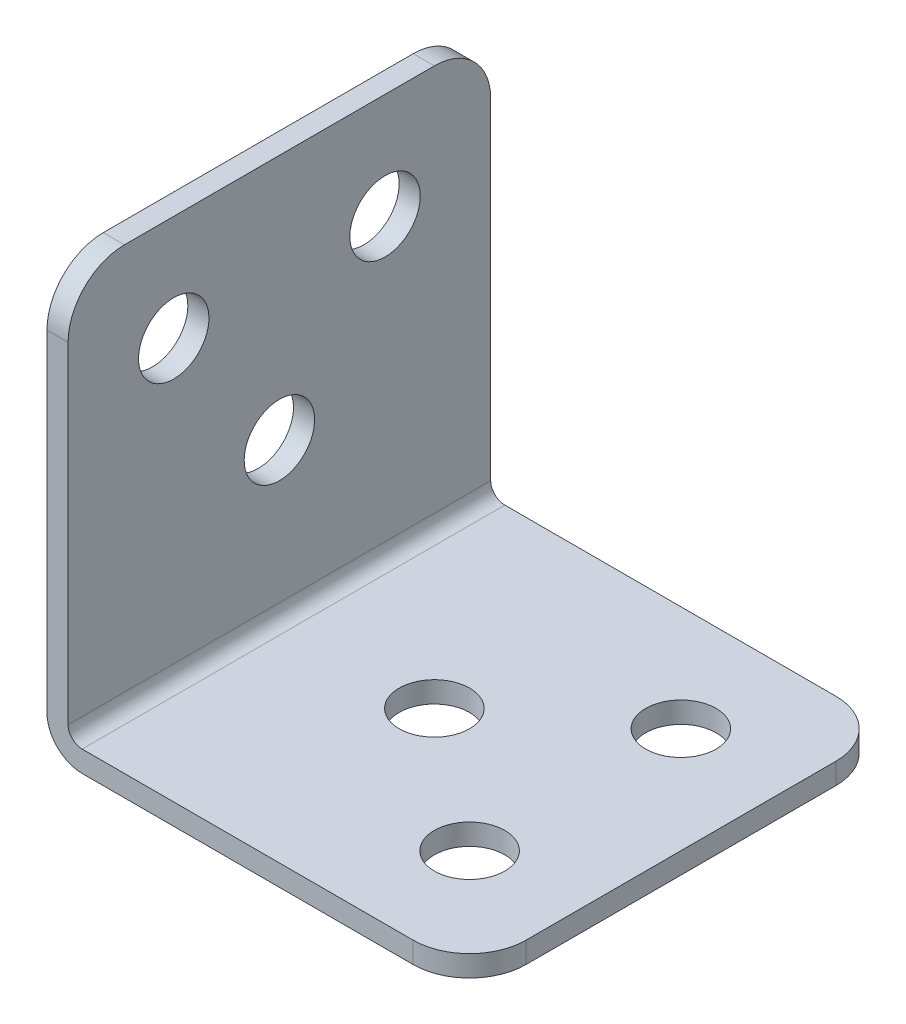
SolidWorks part; units mm, degrees
material "AISI 316 Отожженная нержавеющая сталь. полоса (SS)"
ref_plane "Спереди XY" through (0, 0, 0) normal (0, 0, 1) x (1, 0, 0)
ref_plane "Сверху XZ" through (0, 0, 0) normal (0, 1, 0) x (1, 0, 0)
ref_plane "Справа ZY" through (0, 0, 0) normal (1, 0, 0) x (0, 0, -1)
sketch "Эскиз1" plane through (0, 0, 0) normal (0, 0, 1) x (1, 0, 0)
  line L0 (-2.5, 27.5) -> (-2.5, 0)
  line L1 (0, -2.5) -> (27.5, -2.5)
  line L2 (-1, 27.5) -> (-1, 0)
  line L3 (0, -1) -> (27.5, -1)
  line L4 (-2.5, 27.5) -> (-1, 27.5)
  line L5 (27.5, -1) -> (27.5, -2.5)
  arc A0 (-2.5, 0) -> (0, -2.5) centre (0, 0) ccw
  arc A1 (-1, 0) -> (0, -1) centre (0, 0) ccw
  dimension "D4" = 1
  dimension "D1" = 30
  dimension "D2" = 30
  dimension "D3" = 1.5
extrude "Бобышка-Вытянуть1" add sketch "Эскиз1" along normal blind 30
sketch "Эскиз2" plane through (-2.5, 0, 0) normal (-1, 0, 0) x (0, 0, 1)
  line L0 (15, 27.5) -> (15, -9.5944) construction
  line L1 (30, 27.5) -> (0, 27.5) construction
  line L2 (15, 20) -> (0, 20) construction
  line L6 (0, 27.5) -> (0, 0) construction
  line L7 (30, 27.5) -> (0, 27.5) construction
  circle A0 centre (7.5, 20) radius 2.5
  circle A1 centre (22.5, 20) radius 2.5
  circle A2 centre (15, 10) radius 2.5
  dimension "D1" = 5
  dimension "D4" = 5
  dimension "D2" = 7.5
  dimension "D3" = 17.5
extrude "Вырез-Вытянуть1" cut sketch "Эскиз2" against normal blind 40
sketch "Эскиз3" plane through (0, -2.5, 0) normal (0, -1, 0) x (1, 0, 0)
  line L0 (0, 15) -> (27.5, 15) construction
  line L1 (0, 30) -> (0, 0) construction
  line L2 (27.5, 30) -> (27.5, 0) construction
  line L3 (20, 15) -> (20, 0) construction
  line L5 (0, 0) -> (27.5, 0) construction
  line L6 (27.5, 30) -> (27.5, 0) construction
  circle A0 centre (20, 7.5) radius 2.5
  circle A1 centre (20, 22.5) radius 2.5
  circle A2 centre (10, 15) radius 2.5
  dimension "D1" = 5
  dimension "D3" = 5
  dimension "D2" = 7.5
  dimension "D4" = 17.5
extrude "Вырез-Вытянуть2" cut sketch "Эскиз3" against normal blind 40
fillet "Скругление1" radius 4 4 edges at (27.5, -1.75, 0) (27.5, -1.75, 30) (-1.75, 27.5, 30) (-1.75, 27.5, 0)
